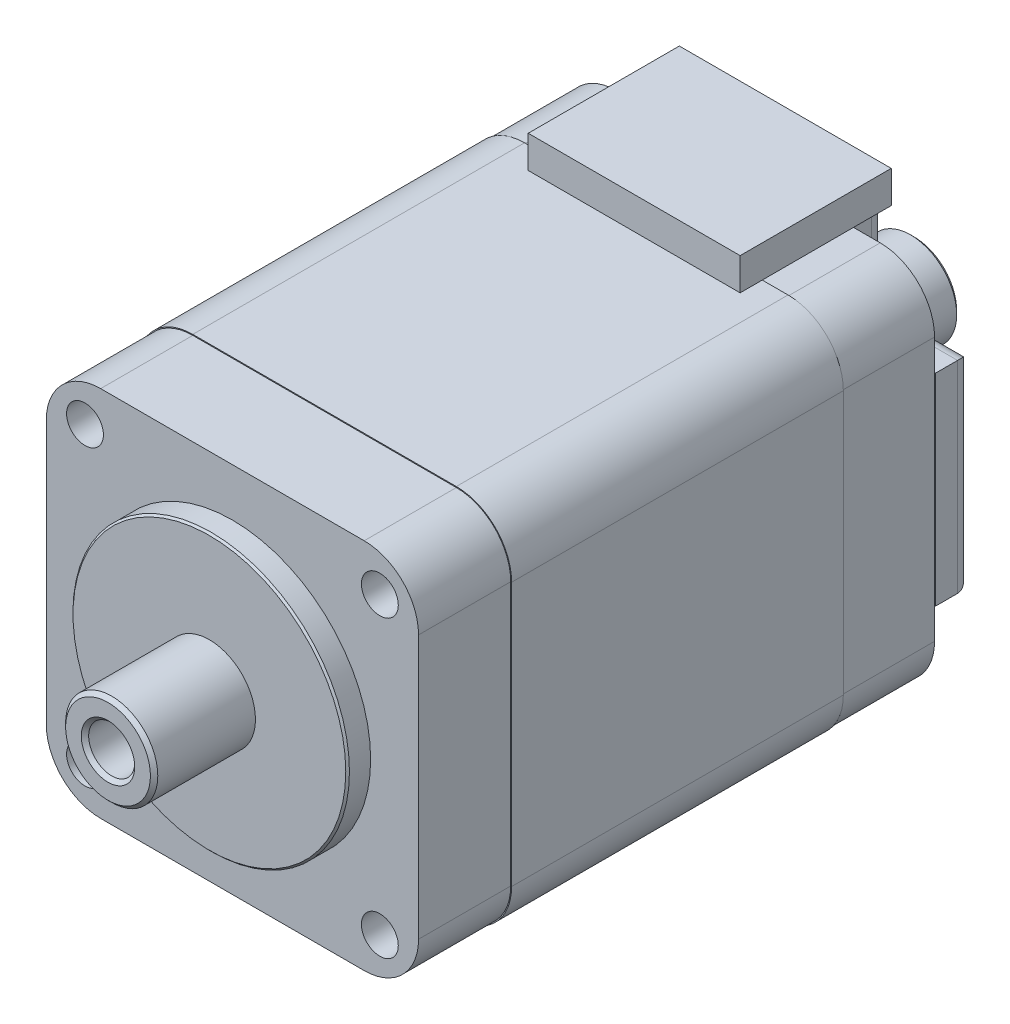
SolidWorks part; units mm, degrees
ref_plane "Front Plane" through (0, 0, 0) normal (0, 0, 1) x (1, 0, 0)
ref_plane "Top Plane" through (0, 0, 0) normal (0, 1, 0) x (1, 0, 0)
ref_plane "Right Plane" through (0, 0, 0) normal (1, 0, 0) x (0, 0, -1)
sketch "Sketch1" plane through (0, 0, 0) normal (1, 0, 0) x (0, 0, -1)
  line L1 (-14, -10.15) -> (14, -10.15)
  line L2 (-14, -10.15) -> (-14, 10.15)
  line L3 (-14, 10.15) -> (14, 10.15)
  line L4 (14, -10.15) -> (14, 10.15)
  line L5 (-14, -10.15) -> (14, 10.15) construction
  line L6 (-14, 10.15) -> (14, -10.15) construction
  point P0 (0, 0)
  dimension "D1" = 28
  dimension "D2" = 20.3
extrude "Boss-Extrude1" add sketch "Sketch1" along normal mid plane 20.3
sketch "Sketch2" plane through (0, 0, 14) normal (0, 0, 1) x (1, 0, 0)
  circle A0 centre (0, 0) radius 7.5
  dimension "D1" = 15
extrude "Boss-Extrude2" add sketch "Sketch2" along normal blind 1.25
sketch "Sketch3" plane through (0, 0, 15.25) normal (0, 0, 1) x (1, 0, 0)
  circle A0 centre (0, 0) radius 2.5
  dimension "D1" = 5
extrude "Boss-Extrude3" add sketch "Sketch3" along normal blind 5.5
sketch "Sketch4" plane through (0, 0, 20.75) normal (0, 0, 1) x (1, 0, 0)
  circle A0 centre (0, 0) radius 1.25
  dimension "D1" = 2.5
extrude "Cut-Extrude1" cut sketch "Sketch4" against normal through all both and the other way through all
chamfer "Chamfer1" distance 0.2 angle 45 1 edges at (1.25, 0, 20.75)
sketch "Sketch6" plane through (0, 0, -14) normal (0, 0, -1) x (-1, 0, 0)
  circle A0 centre (0, 0) radius 2.5
  circle A1 centre (0, 0) radius 1.25 construction
  circle A2 centre (0, 0) radius 1.25
  dimension "D1" = 5
extrude "Boss-Extrude4" add sketch "Sketch6" along normal blind 9
chamfer "Chamfer4" distance 0.2 angle 45 2 edges at (-1.25, 0, -23) (-2.5, 0, -23)
sketch "Sketch7" plane through (0, 0, 14) normal (0, 0, 1) x (1, 0, 0)
  line L2 (-8, 8) -> (8, 8) construction
  line L3 (-8, 8) -> (-8, -8) construction
  line L4 (-8, -8) -> (8, -8) construction
  line L5 (8, 8) -> (8, -8) construction
  line L6 (-8, 8) -> (8, -8) construction
  line L7 (-8, -8) -> (8, 8) construction
  circle A0 centre (-8, 8) radius 1
  circle A1 centre (8, 8) radius 1
  circle A2 centre (8, -8) radius 1
  circle A3 centre (-8, -8) radius 1
  point P0 (0, 0)
  dimension "D3" = 2
  dimension "D1" = 16
  dimension "D2" = 16
extrude "Cut-Extrude2" cut sketch "Sketch7" against normal through all
fillet "Fillet1" radius 3 4 edges at (10.15, 10.15, 0) (10.15, -10.15, 0) (-10.15, -10.15, 0) (-10.15, 10.15, 0)
sketch "Sketch10" plane through (0, 0, -14) normal (0, 0, -1) x (-1, 0, 0)
  line L0 (-7.7, 5.475) -> (-10.15, 5.475)
  line L1 (-10.15, -7.15) -> (-10.15, 7.15) construction
  line L2 (-10.15, 5.475) -> (-10.15, -5.475)
  line L3 (-10.15, -5.475) -> (-7.7, -5.475)
  line L4 (-5.475, -7.7) -> (-5.475, -10.15)
  line L5 (-7.15, -10.15) -> (7.15, -10.15) construction
  line L6 (-5.475, -10.15) -> (5.475, -10.15)
  line L7 (5.475, -10.15) -> (5.475, -7.7)
  line L8 (7.7, -5.475) -> (10.15, -5.475)
  line L9 (10.15, -7.15) -> (10.15, 7.15) construction
  line L10 (10.15, -5.475) -> (10.15, 5.475)
  line L11 (10.15, 5.475) -> (7.7, 5.475)
  line L12 (-5.475, 7.7) -> (-5.475, 10.15)
  line L13 (-7.15, 10.15) -> (7.15, 10.15) construction
  line L14 (-5.475, 10.15) -> (5.475, 10.15)
  line L15 (5.475, 10.15) -> (5.475, 7.7)
  arc A0 (-7.7, -5.475) -> (-5.475, -7.7) centre (-7.7, -7.7) cw
  arc A1 (5.475, -7.7) -> (7.7, -5.475) centre (7.7, -7.7) cw
  arc A2 (7.7, 5.475) -> (5.475, 7.7) centre (7.7, 7.7) cw
  arc A3 (-5.475, 7.7) -> (-7.7, 5.475) centre (-7.7, 7.7) cw
  circle A17 centre (0, 0) radius 2.6
  circle A18 centre (0, 0) radius 2.6
  dimension "D5" = 0.1
extrude "Boss-Extrude5" add sketch "Sketch10" along normal blind 2 separate body
fillet "Fillet2" radius 0.8 15 edges at (-5.475, 8.925, -16) (-8.925, 5.475, -16) (-10.15, 0, -16) (-5.475, -8.925, -16) (-8.925, -5.475, -16) (0, -10.15, -16) (5.475, -8.925, -16) (8.925, -5.475, -16) (10.15, 0, -16) (8.925, 5.475, -16) (5.475, 8.925, -16) (-6.1267, 6.1267, -16) (-6.1267, -6.1267, -16) (6.1267, -6.1267, -16) (6.1267, 6.1267, -16)
sketch "Sketch13" plane through (0, 10.15, 0) normal (0, 1, 0) x (1, 0, 0)
  line L1 (5.75, 16) -> (-5.75, 16)
  line L2 (5.75, 16) -> (5.75, 7.8)
  line L3 (5.75, 7.8) -> (-5.75, 7.8)
  line L4 (-5.75, 16) -> (-5.75, 7.8)
  line L5 (5.75, 16) -> (-5.75, 7.8) construction
  line L6 (5.75, 7.8) -> (-5.75, 16) construction
  line L8 (2.6, 16) -> (-2.6, 16) construction
  point P0 (0, 11.9)
  dimension "D1" = 11.5
  dimension "D2" = 8.2
extrude "Boss-Extrude7" add sketch "Sketch13" along normal blind 1.75
sketch "Sketch14" plane through (0, 0, 14) normal (0, 0, 1) x (1, 0, 0)
  line L8 (10.1, -7.15) -> (10.1, 7.15)
  line L9 (7.15, 10.1) -> (-7.15, 10.1)
  line L10 (-10.1, 7.15) -> (-10.1, -7.15)
  line L11 (-7.15, -10.1) -> (7.15, -10.1)
  line L12 (10.1, -7.15) -> (10.1, 7.15)
  line L13 (7.15, 10.1) -> (-7.15, 10.1)
  line L14 (-10.1, 7.15) -> (-10.1, -7.15)
  line L15 (-7.15, -10.1) -> (7.15, -10.1)
  line L16 (10.15, -7.15) -> (10.15, 7.15)
  line L17 (7.15, 10.15) -> (-7.15, 10.15)
  line L18 (-10.15, 7.15) -> (-10.15, -7.15)
  line L19 (-7.15, -10.15) -> (7.15, -10.15)
  line L20 (10.15, -7.15) -> (10.15, 7.15)
  line L21 (7.15, 10.15) -> (-7.15, 10.15)
  line L22 (-10.15, 7.15) -> (-10.15, -7.15)
  line L23 (-7.15, -10.15) -> (7.15, -10.15)
  arc A8 (10.1, 7.15) -> (7.15, 10.1) centre (7.15, 7.15) ccw
  arc A9 (-7.15, 10.1) -> (-10.1, 7.15) centre (-7.15, 7.15) ccw
  arc A10 (-10.1, -7.15) -> (-7.15, -10.1) centre (-7.15, -7.15) ccw
  arc A11 (7.15, -10.1) -> (10.1, -7.15) centre (7.15, -7.15) ccw
  arc A12 (10.1, 7.15) -> (7.15, 10.1) centre (7.15, 7.15) ccw
  arc A13 (-7.15, 10.1) -> (-10.1, 7.15) centre (-7.15, 7.15) ccw
  arc A14 (-10.1, -7.15) -> (-7.15, -10.1) centre (-7.15, -7.15) ccw
  arc A15 (7.15, -10.1) -> (10.1, -7.15) centre (7.15, -7.15) ccw
  arc A16 (10.15, 7.15) -> (7.15, 10.15) centre (7.15, 7.15) ccw
  arc A17 (-7.15, 10.15) -> (-10.15, 7.15) centre (-7.15, 7.15) ccw
  arc A18 (-10.15, -7.15) -> (-7.15, -10.15) centre (-7.15, -7.15) ccw
  arc A19 (7.15, -10.15) -> (10.15, -7.15) centre (7.15, -7.15) ccw
  arc A20 (10.15, 7.15) -> (7.15, 10.15) centre (7.15, 7.15) ccw
  arc A21 (-7.15, 10.15) -> (-10.15, 7.15) centre (-7.15, 7.15) ccw
  arc A22 (-10.15, -7.15) -> (-7.15, -10.15) centre (-7.15, -7.15) ccw
  arc A23 (7.15, -10.15) -> (10.15, -7.15) centre (7.15, -7.15) ccw
  dimension "D1" = 0.05
  dimension "D2" = 0
extrude "Cut-Extrude5" cut sketch "Sketch14" against normal blind 5
sketch "Sketch15" plane through (0, 0, -14) normal (0, 0, -1) x (-1, 0, 0)
  line L4 (-10.1, 7.15) -> (-10.1, -7.15)
  line L5 (7.15, 10.1) -> (-7.15, 10.1)
  line L6 (10.1, -7.15) -> (10.1, 7.15)
  line L7 (-7.15, -10.1) -> (7.15, -10.1)
  line L8 (-10.1, 7.15) -> (-10.1, -7.15)
  line L9 (7.15, 10.1) -> (-7.15, 10.1)
  line L10 (10.1, -7.15) -> (10.1, 7.15)
  line L11 (-7.15, -10.1) -> (7.15, -10.1)
  line L12 (7.15, 10.15) -> (5.75, 10.15)
  line L13 (-10.15, 7.15) -> (-10.15, -7.15)
  line L14 (-7.15, -10.15) -> (7.15, -10.15)
  line L15 (10.15, -7.15) -> (10.15, 7.15)
  line L16 (7.15, 10.15) -> (5.75, 10.15)
  line L17 (-10.15, 7.15) -> (-10.15, -7.15)
  line L18 (-7.15, -10.15) -> (7.15, -10.15)
  line L19 (10.15, -7.15) -> (10.15, 7.15)
  line L22 (-5.75, 10.15) -> (-7.15, 10.15)
  line L23 (-5.75, 10.15) -> (-7.15, 10.15)
  line L24 (5.75, 10.15) -> (-5.75, 10.15)
  line L25 (5.75, 10.15) -> (-5.75, 10.15)
  arc A4 (-10.1, -7.15) -> (-7.15, -10.1) centre (-7.15, -7.15) ccw
  arc A5 (-7.15, 10.1) -> (-10.1, 7.15) centre (-7.15, 7.15) ccw
  arc A6 (10.1, 7.15) -> (7.15, 10.1) centre (7.15, 7.15) ccw
  arc A7 (7.15, -10.1) -> (10.1, -7.15) centre (7.15, -7.15) ccw
  arc A8 (-10.1, -7.15) -> (-7.15, -10.1) centre (-7.15, -7.15) ccw
  arc A9 (-7.15, 10.1) -> (-10.1, 7.15) centre (-7.15, 7.15) ccw
  arc A10 (10.1, 7.15) -> (7.15, 10.1) centre (7.15, 7.15) ccw
  arc A11 (7.15, -10.1) -> (10.1, -7.15) centre (7.15, -7.15) ccw
  arc A12 (-7.15, 10.15) -> (-10.15, 7.15) centre (-7.15, 7.15) ccw
  arc A13 (-10.15, -7.15) -> (-7.15, -10.15) centre (-7.15, -7.15) ccw
  arc A14 (7.15, -10.15) -> (10.15, -7.15) centre (7.15, -7.15) ccw
  arc A15 (10.15, 7.15) -> (7.15, 10.15) centre (7.15, 7.15) ccw
  arc A16 (-7.15, 10.15) -> (-10.15, 7.15) centre (-7.15, 7.15) ccw
  arc A17 (-10.15, -7.15) -> (-7.15, -10.15) centre (-7.15, -7.15) ccw
  arc A18 (7.15, -10.15) -> (10.15, -7.15) centre (7.15, -7.15) ccw
  arc A19 (10.15, 7.15) -> (7.15, 10.15) centre (7.15, 7.15) ccw
  dimension "D1" = 0
  dimension "D2" = 0
extrude "Cut-Extrude6" cut sketch "Sketch15" against normal blind 5
chamfer "Chamfer5" distance 0.1 angle 45 1 edges at (7.5, 0, 15.25)
